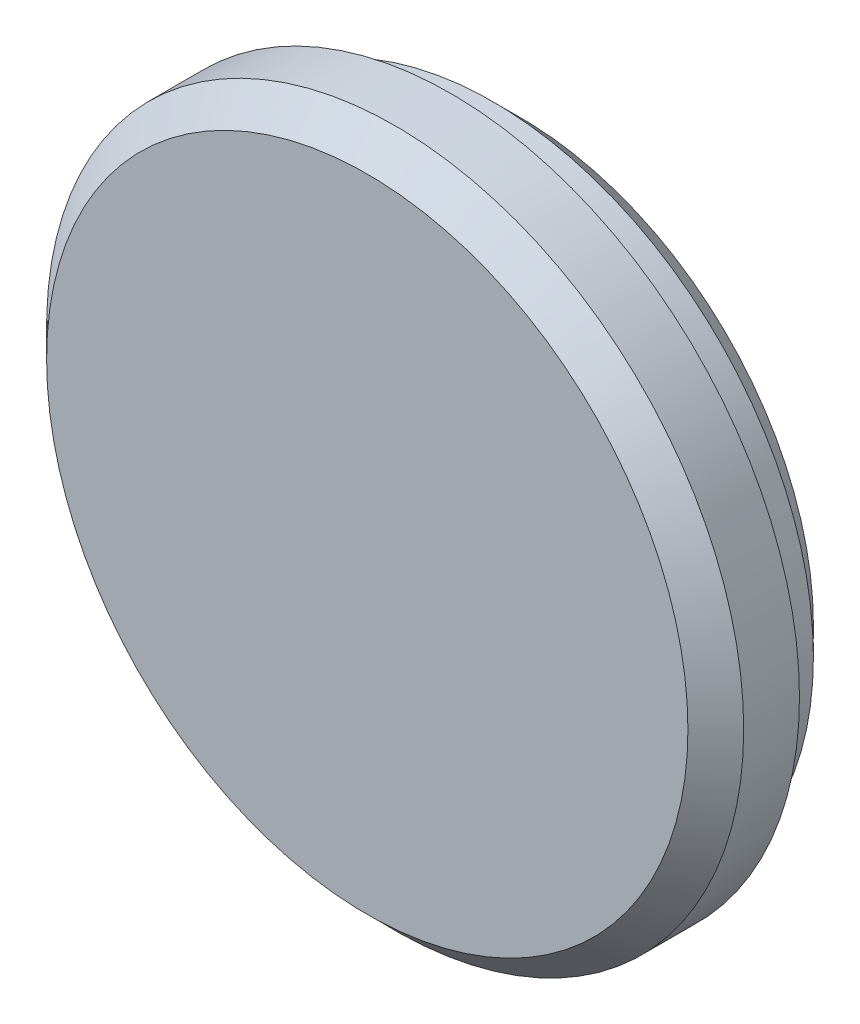
SolidWorks part; units mm, degrees
ref_plane "Front Plane" through (0, 0, 0) normal (0, 0, 1) x (1, 0, 0)
ref_plane "Top Plane" through (0, 0, 0) normal (0, 1, 0) x (1, 0, 0)
ref_plane "Right Plane" through (0, 0, 0) normal (1, 0, 0) x (0, 0, -1)
sketch "Sketch1" plane through (0, 0, 0) normal (0, 0, 1) x (1, 0, 0)
  circle A0 centre (0, 0) radius 12.5
  dimension "D1" = 25
extrude "Corpo" add sketch "Sketch1" against normal blind 3
sketch "Sketch2" plane through (0, 0, -3) normal (0, 0, -1) x (-1, 0, 0)
  circle A0 centre (0, 0) radius 8.5
  circle A3 centre (0, 0) radius 11.5
  dimension "D1" = 17
  dimension "D2" = 3
extrude "Eixo de Encaixe - Ø20" add sketch "Sketch2" along normal blind 2.5
chamfer "Chanfro 1x45°" distance 1 angle 45 3 edges at (12.5, 0, 0) (-8.5, 0, -5.5) (-11.5, 0, -5.5)
